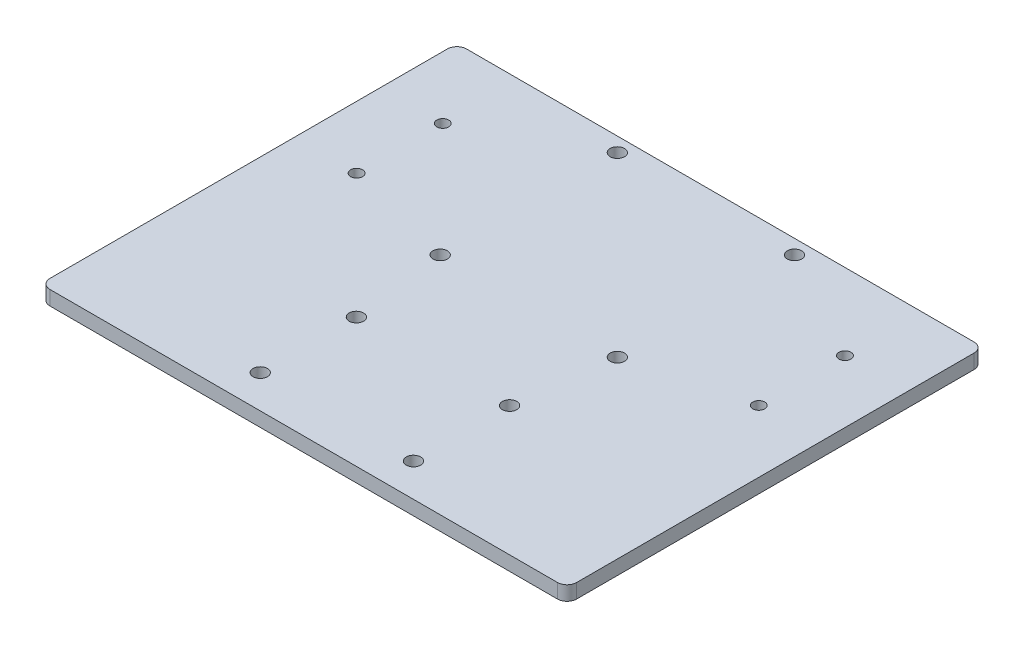
SolidWorks part; units mm, degrees
ref_plane "Ön Düzlem" through (0, 0, 0) normal (0, 0, 1) x (1, 0, 0)
ref_plane "Üst Düzlem" through (0, 0, 0) normal (0, 1, 0) x (1, 0, 0)
ref_plane "Sağ Düzlem" through (0, 0, 0) normal (1, 0, 0) x (0, 0, -1)
sketch "Çizim1" plane through (0, 0, 0) normal (0, 1, 0) x (1, 0, 0)
  line L1 (-55, -43.5) -> (55, -43.5)
  line L2 (-55, -43.5) -> (-55, 43.5)
  line L3 (-55, 43.5) -> (55, 43.5)
  line L4 (55, -43.5) -> (55, 43.5)
  line L5 (-55, -43.5) -> (55, 43.5) construction
  line L6 (-55, 43.5) -> (55, -43.5) construction
  point P0 (0, 0)
  dimension "D1" = 110
  dimension "D2" = 87
extrude "Yükseklik-Ekstrüzyon1" add sketch "Çizim1" along normal blind 3
fillet "Radyus1" radius 2 4 edges at (-55, 1.5, -43.5) (55, 1.5, -43.5) (55, 1.5, 43.5) (-55, 1.5, 43.5)
sketch "Çizim2" plane through (0, 3, 0) normal (0, 1, 0) x (1, 0, 0)
  line L0 (-55, 41.5) -> (-55, -41.5) construction
  line L1 (53, 43.5) -> (-53, 43.5) construction
  line L2 (55, -41.5) -> (55, 41.5) construction
  line L3 (-53, -43.5) -> (53, -43.5) construction
  circle A0 centre (-18.5, 40.5) radius 1.5
  circle A1 centre (18.5, 40.5) radius 1.5
  circle A2 centre (18.5, 3.5) radius 1.5
  circle A3 centre (-18.5, 3.5) radius 1.5
  circle A4 centre (-42, 27.54) radius 1.25
  circle A5 centre (-42, 9.54) radius 1.25
  circle A6 centre (42, 27.54) radius 1.25
  circle A7 centre (42, 9.54) radius 1.25
  circle A8 centre (-16, -36.58) radius 1.5
  circle A9 centre (-16, -16.5) radius 1.5
  circle A10 centre (16, -16.5) radius 1.5
  circle A11 centre (16, -36.58) radius 1.5
  dimension "D1" = 3
  dimension "D2" = 3
  dimension "D3" = 3
  dimension "D4" = 3
  dimension "D11" = 2.5
  dimension "D12" = 2.5
  dimension "D16" = 2.5
  dimension "D17" = 2.5
  dimension "D21" = 3
  dimension "D22" = 3
  dimension "D23" = 3
  dimension "D24" = 3
  dimension "D5" = 36.5
  dimension "D6" = 3
  dimension "D7" = 3
  dimension "D8" = 37
  dimension "D9" = 37
  dimension "D10" = 37
  dimension "D13" = 13
  dimension "D14" = 15.96
  dimension "D15" = 18
  dimension "D18" = 15.96
  dimension "D19" = 18
  dimension "D20" = 13
  dimension "D25" = 6.92
  dimension "D26" = 32
  dimension "D27" = 20.08
  dimension "D28" = 39
extrude "Kes-Ekstrüzyon1" cut sketch "Çizim2" against normal blind 10
